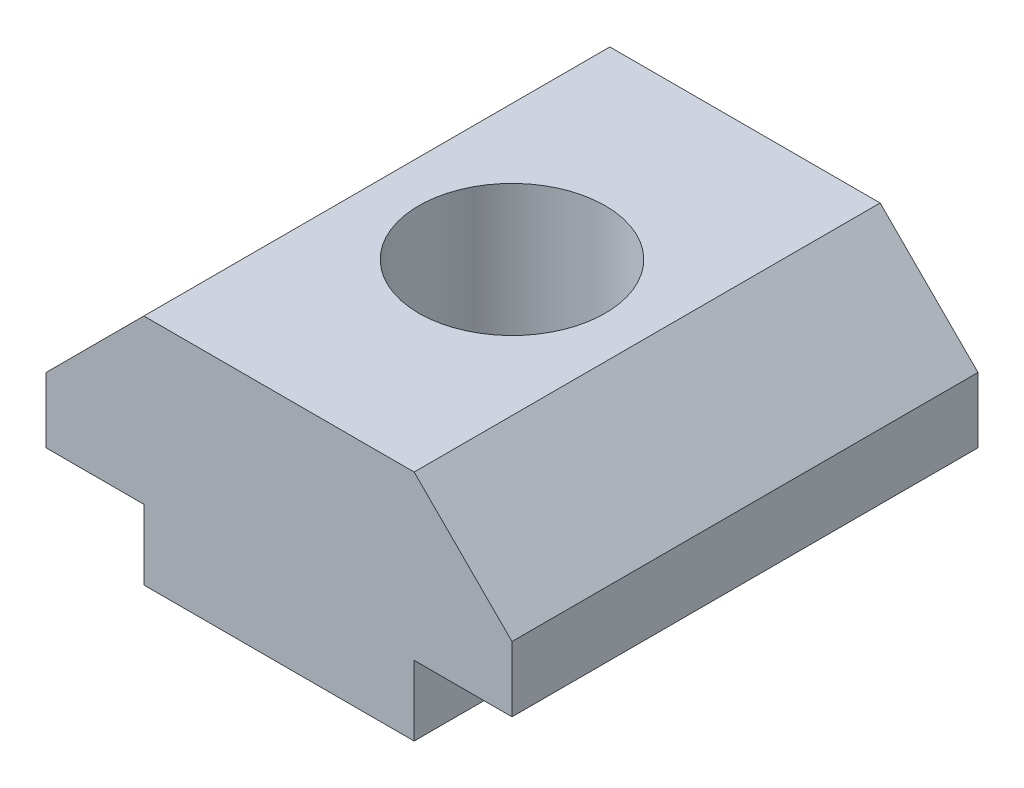
SolidWorks part; units mm, degrees
ref_plane "前视基准面" through (0, 0, 0) normal (0, 0, 1) x (1, 0, 0)
ref_plane "上视基准面" through (0, 0, 0) normal (0, 1, 0) x (1, 0, 0)
ref_plane "右视基准面" through (0, 0, 0) normal (1, 0, 0) x (0, 0, -1)
sketch "草图1" plane through (0, 0, 0) normal (0, 0, 1) x (1, 0, 0)
  line L0 (-2.9, 0) -> (2.9, 0)
  line L1 (2.9, 0) -> (2.9, 1.5)
  line L2 (2.9, 1.5) -> (5, 1.5)
  line L3 (5, 1.5) -> (5, 2.9)
  line L4 (5, 2.9) -> (2.9, 5)
  line L5 (2.9, 5) -> (-2.9, 5)
  line L6 (-2.9, 5) -> (-5, 2.9)
  line L7 (-5, 2.9) -> (-5, 1.5)
  line L8 (-5, 1.5) -> (-2.9, 1.5)
  line L9 (-2.9, 1.5) -> (-2.9, 0)
  line L10 (0, -82.6522) -> (0, 4049.9602) construction
  point P14 (0, 0)
  point P17 (-5, 2.2)
  dimension "D1" = 5.8
  dimension "D2" = 5
  dimension "D3" = 10
  dimension "D4" = 135
  dimension "D5" = 1.5
extrude "凸台-拉伸1" add sketch "草图1" against normal blind 10
sketch "草图4" plane through (0, 5, 0) normal (0, 1, 0) x (1, 0, 0)
  line L0 (0, -990) -> (0, 49010) construction
  line L1 (2.9, 10) -> (-2.9, 10) construction
  line L2 (-995.1, 5) -> (49004.9, 5) construction
  line L3 (5, 10) -> (5, 0) construction
  circle A0 centre (0, 5) radius 2
  point P5 (0, 10)
  point P10 (5, 5)
  dimension "D1" = 4
extrude "切除-拉伸1" cut sketch "草图4" against normal through all
